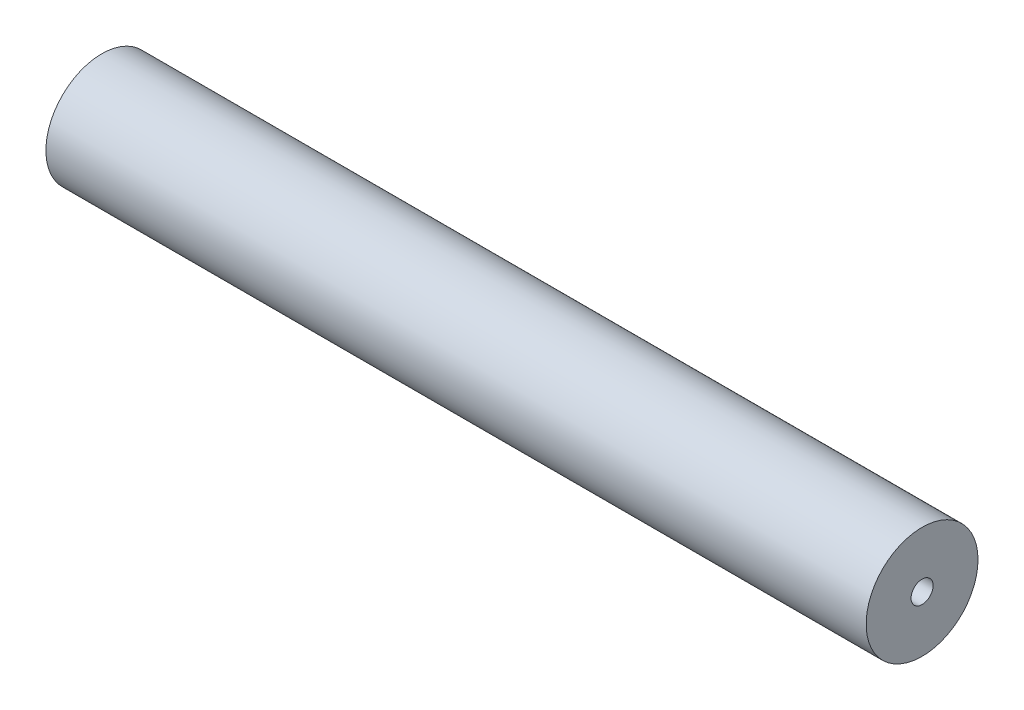
SolidWorks part; units mm, degrees
ref_plane "Front Plane" through (0, 0, 0) normal (0, 0, 1) x (1, 0, 0)
ref_plane "Top Plane" through (0, 0, 0) normal (0, 1, 0) x (1, 0, 0)
ref_plane "Right Plane" through (0, 0, 0) normal (1, 0, 0) x (0, 0, -1)
sketch "Sketch1" plane through (0, 0, 0) normal (1, 0, 0) x (0, 0, -1)
  circle A0 centre (0, 0) radius 38.1
  dimension "D1" = 76.2
extrude "Boss-Extrude1" add sketch "Sketch1" along normal blind 558.8
sketch "Sketch3" plane through (0, 0, 0) normal (-1, 0, 0) x (0, 0, 1)
  circle A0 centre (0, 0) radius 12.7
  dimension "D1" = 25.4
hole_wizard "M12 Clearance Hole1" positions "Sketch4" profile "Sketch5" hole size "M12" standard "ANSI Metric"
sketch "Sketch4" plane through (0, 0, 0) normal (-1, 0, 0) x (0, 0, 1)
  point P0 (0, 0)
sketch "Sketch5" plane through (0, 0, 0) normal (0, 1, 0) x (0, 0, 1)
  line L0 (0, 0) -> (0, 25.4)
  line L1 (0, 25.4) -> (6.75, 21.3442)
  line L2 (6.75, 21.3442) -> (6.75, 0.025)
  line L3 (6.75, 0.025) -> (6.775, 0)
  line L5 (6.775, 0) -> (0, 0)
  line L6 (-6.75, 0.025) -> (-6.775, 0) construction
  line L10 (0, 25.4) -> (-6.75, 21.3442) construction
  line L11 (0, -6.35) -> (0, 107.95) construction
  dimension "Hole Dia." = 13.5
  dimension "Hole Depth" = 25.4
  dimension "Near C'Sink Dia." = 13.55
  dimension "Near C'Sink Angle" = 90
  dimension "Drill Angle" = 118
hole_wizard "M12 Clearance Hole2" positions "Sketch8" profile "Sketch9" hole size "M12" standard "ANSI Metric"
sketch "Sketch8" plane through (558.8, 0, 0) normal (1, 0, 0) x (0, 0, -1)
  point P0 (0, 0)
sketch "Sketch9" plane through (558.8, 0, 0) normal (0, 1, 0) x (0, 0, -1)
  line L0 (0, 0) -> (0, 25.4)
  line L1 (0, 25.4) -> (7.5, 20.8935)
  line L2 (7.5, 20.8935) -> (7.5, 0)
  line L5 (7.5, 0) -> (0, 0)
  line L10 (0, 25.4) -> (-7.5, 20.8935) construction
  line L11 (0, -6.35) -> (0, 107.95) construction
  dimension "Hole Dia." = 15
  dimension "Hole Depth" = 25.4
  dimension "Drill Angle" = 118
